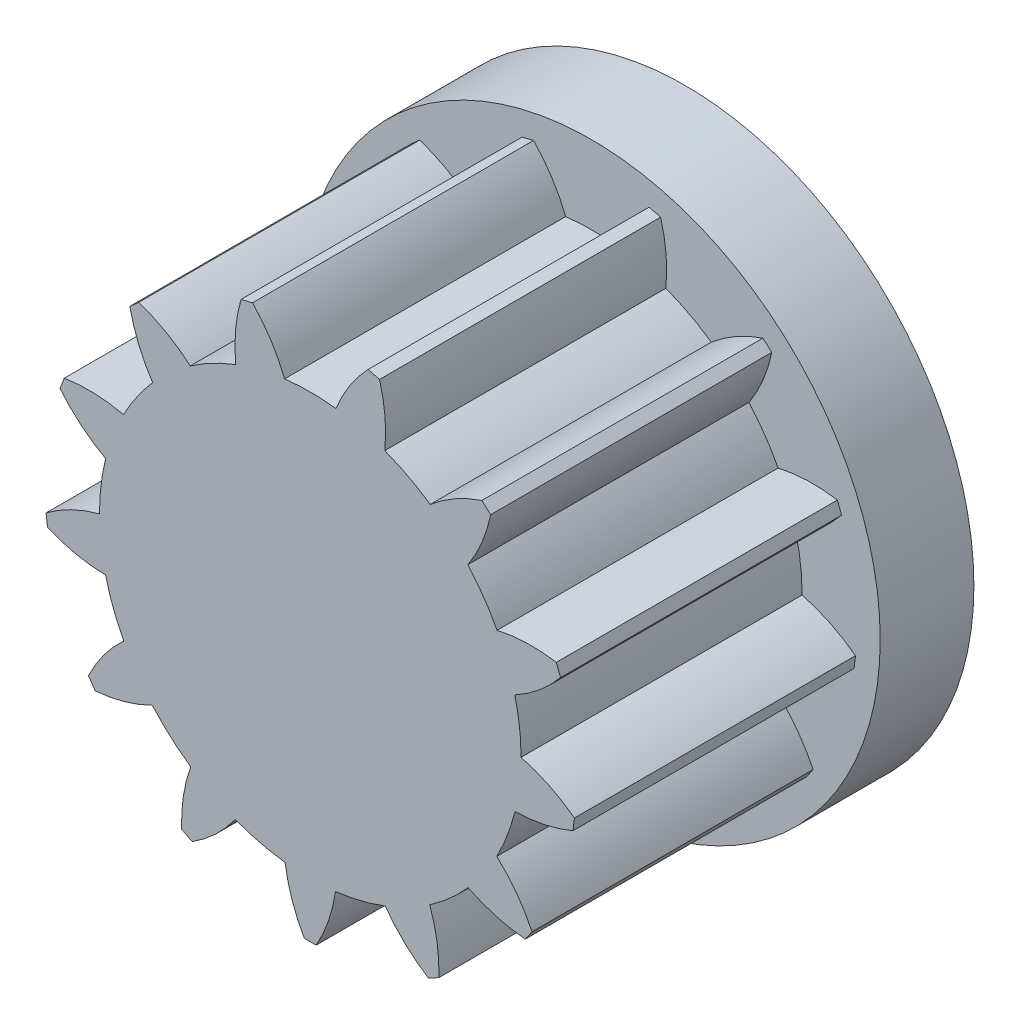
SolidWorks part; units mm, degrees
ref_plane "Front Plane" through (0, 0, 0) normal (0, 0, 1) x (1, 0, 0)
ref_plane "Top Plane" through (0, 0, 0) normal (0, 1, 0) x (1, 0, 0)
ref_plane "Right Plane" through (0, 0, 0) normal (1, 0, 0) x (0, 0, -1)
sketch "Sketch1" plane through (0, 0, 0) normal (0, 0, 1) x (1, 0, 0)
  circle A0 centre (0, 0) radius 9.25
  dimension "D1" = 18.5
extrude "Boss-Extrude1" add sketch "Sketch1" along normal blind 3
sketch "Sketch2" plane through (0, 0, 3) normal (0, 0, 1) x (1, 0, 0)
  line L0 (14.2339, 0) -> (6.75, 0) construction
  line L1 (0, -10.1027) -> (0, -7.2907)
  line L2 (0, 0) -> (2.7187, 11.027) construction
  line L3 (2.2187, 8.2053) -> (1.8498, 8.2963)
  line L4 (5.7778, 6.2344) -> (5.4934, 6.4864)
  line L5 (8.0132, 2.8352) -> (7.8785, 3.1905)
  line L6 (8.4129, -1.2135) -> (8.4588, -0.8363)
  line L7 (6.8853, -4.9842) -> (7.1012, -4.6715)
  line L8 (3.7804, -7.613) -> (4.1169, -7.4365)
  line L9 (-0.1906, -8.4979) -> (0.1894, -8.4979)
  line L10 (-4.1179, -7.4359) -> (-3.7814, -7.6125)
  line L11 (-7.1019, -4.6705) -> (-6.886, -4.9832)
  line L12 (-8.4589, -0.8351) -> (-8.4131, -1.2124)
  line L13 (-7.8781, 3.1916) -> (-8.0128, 2.8363)
  line L14 (-5.4925, 6.4871) -> (-5.7769, 6.2351)
  line L15 (-1.8486, 8.2965) -> (-2.2176, 8.2056)
  line L16 (-6.75, 0) -> (-12.8697, 0) construction
  line L17 (0, 6.75) -> (0, 9.8196)
  arc A0 (-5.4925, 6.4871) -> (-5.7769, 6.2351) centre (0, 0) ccw
  arc A1 (-5.0464, 4.4829) -> (-5.9806, 3.1296) centre (0, 0) ccw
  circle A2 centre (0, 0) radius 7.2907 construction
  circle A3 centre (0, 0) radius 7.7444 construction
  arc A5 (2.3859, 6.3143) -> (2.2187, 8.2053) centre (-2.5478, 6.831) ccw
  arc A6 (0.8227, 6.6997) -> (1.8498, 8.2963) centre (5.4311, 4.8638) cw
  arc A7 (5.047, 4.4822) -> (5.7778, 6.2344) centre (0.9186, 7.2326) ccw
  arc A8 (3.842, 5.5499) -> (5.4934, 6.4864) centre (7.0694, 1.7827) cw
  arc A9 (6.5519, 1.6234) -> (8.0132, 2.8352) centre (4.1745, 5.9772) ccw
  arc A10 (5.9811, 3.1288) -> (7.8785, 3.1905) centre (7.0881, -1.7068) cw
  arc A11 (6.5558, -1.6074) -> (8.4129, -1.2135) centre (6.4741, 3.3526) ccw
  arc A12 (6.75, -0.0091) -> (8.4588, -0.8363) centre (5.483, -4.8053) cw
  arc A13 (5.0579, -4.4699) -> (6.8853, -4.9842) centre (7.2906, -0.0401) ccw
  arc A14 (5.9726, -3.145) -> (7.1012, -4.6715) centre (2.6219, -6.8029) cw
  arc A15 (2.4013, -6.3084) -> (3.7804, -7.613) centre (6.4368, -3.4236) ccw
  arc A16 (3.8269, -5.5603) -> (4.1169, -7.4365) centre (-0.8399, -7.2421) cw
  arc A17 (-0.8054, -6.7018) -> (-0.1906, -8.4979) centre (4.1085, -6.0228) ccw
  arc A18 (0.8046, -6.7019) -> (0.1894, -8.4979) centre (-4.1093, -6.0223) cw
  arc A19 (-3.8277, -5.5598) -> (-4.1179, -7.4359) centre (0.839, -7.2422) ccw
  arc A20 (-2.4021, -6.3081) -> (-3.7814, -7.6125) centre (-6.4373, -3.4228) cw
  arc A21 (-5.973, -3.1442) -> (-7.1019, -4.6705) centre (-2.6228, -6.8026) ccw
  arc A22 (-5.0585, -4.4692) -> (-6.886, -4.9832) centre (-7.2906, -0.0391) cw
  arc A23 (-6.75, -0.0082) -> (-8.4589, -0.8351) centre (-5.4837, -4.8045) ccw
  arc A24 (-6.556, -1.6065) -> (-8.4131, -1.2124) centre (-6.4737, 3.3534) cw
  arc A25 (-5.9806, 3.1296) -> (-7.8781, 3.1916) centre (-7.0883, -1.7058) ccw
  arc A26 (-6.5517, 1.6243) -> (-8.0128, 2.8363) centre (-4.1737, 5.9778) cw
  arc A27 (-3.8412, 5.5505) -> (-5.4925, 6.4871) centre (-7.0691, 1.7837) ccw
  arc A28 (-5.0464, 4.4829) -> (-5.7769, 6.2351) centre (-0.9176, 7.2327) cw
  arc A29 (-0.8218, 6.6998) -> (-1.8486, 8.2965) centre (-5.4305, 4.8646) ccw
  arc A30 (-2.385, 6.3146) -> (-2.2176, 8.2056) centre (2.5487, 6.8307) cw
  arc A31 (-1.8486, 8.2965) -> (-2.2176, 8.2056) centre (0, 0) ccw
  arc A32 (2.2187, 8.2053) -> (0, 8.5) centre (0, 0) ccw
  arc A33 (5.7778, 6.2344) -> (5.4934, 6.4864) centre (0, 0) ccw
  arc A34 (8.0132, 2.8352) -> (7.8785, 3.1905) centre (0, 0) ccw
  arc A35 (8.4129, -1.2135) -> (8.4588, -0.8363) centre (0, 0) ccw
  arc A36 (-7.8781, 3.1916) -> (-8.0128, 2.8363) centre (0, 0) ccw
  arc A37 (-8.4589, -0.8351) -> (-8.4131, -1.2124) centre (0, 0) ccw
  arc A38 (-7.1019, -4.6705) -> (-6.886, -4.9832) centre (0, 0) ccw
  arc A39 (-4.1179, -7.4359) -> (-3.7814, -7.6125) centre (0, 0) ccw
  arc A40 (6.8853, -4.9842) -> (7.1012, -4.6715) centre (0, 0) ccw
  arc A41 (3.7804, -7.613) -> (4.1169, -7.4365) centre (0, 0) ccw
  arc A42 (-0.1906, -8.4979) -> (0.1894, -8.4979) centre (0, 0) ccw
  arc A43 (-2.385, 6.3146) -> (-3.8412, 5.5505) centre (0, 0) ccw
  arc A44 (0.8227, 6.6997) -> (-0.8218, 6.6998) centre (0, 0) ccw
  arc A45 (3.842, 5.5499) -> (2.3859, 6.3143) centre (0, 0) ccw
  arc A46 (5.9811, 3.1288) -> (5.047, 4.4822) centre (0, 0) ccw
  arc A47 (6.75, -0.0091) -> (6.5519, 1.6234) centre (0, 0) ccw
  arc A48 (5.9726, -3.145) -> (6.5558, -1.6074) centre (0, 0) ccw
  arc A49 (3.8269, -5.5603) -> (5.0579, -4.4699) centre (0, 0) ccw
  arc A50 (0.8046, -6.7019) -> (2.4013, -6.3084) centre (0, 0) ccw
  arc A51 (-2.4021, -6.3081) -> (-0.8054, -6.7018) centre (0, 0) ccw
  arc A52 (-5.0585, -4.4692) -> (-3.8277, -5.5598) centre (0, 0) ccw
  arc A53 (-6.556, -1.6065) -> (-5.973, -3.1442) centre (0, 0) ccw
  arc A54 (-6.5517, 1.6243) -> (-6.75, -0.0082) centre (0, 0) ccw
  point P11 (1.8539, 7.5193)
  dimension "D1" = 17
  dimension "D2" = 13.5
  dimension "D5" = 14.5814
  dimension "D6" = 15.4889
  dimension "D3" = 13.85
  dimension "D4" = 0.805
  dimension "D7" = 0.19
  dimension "D8" = 13
extrude "Boss-Extrude2" add sketch "Sketch2" along normal blind 9
